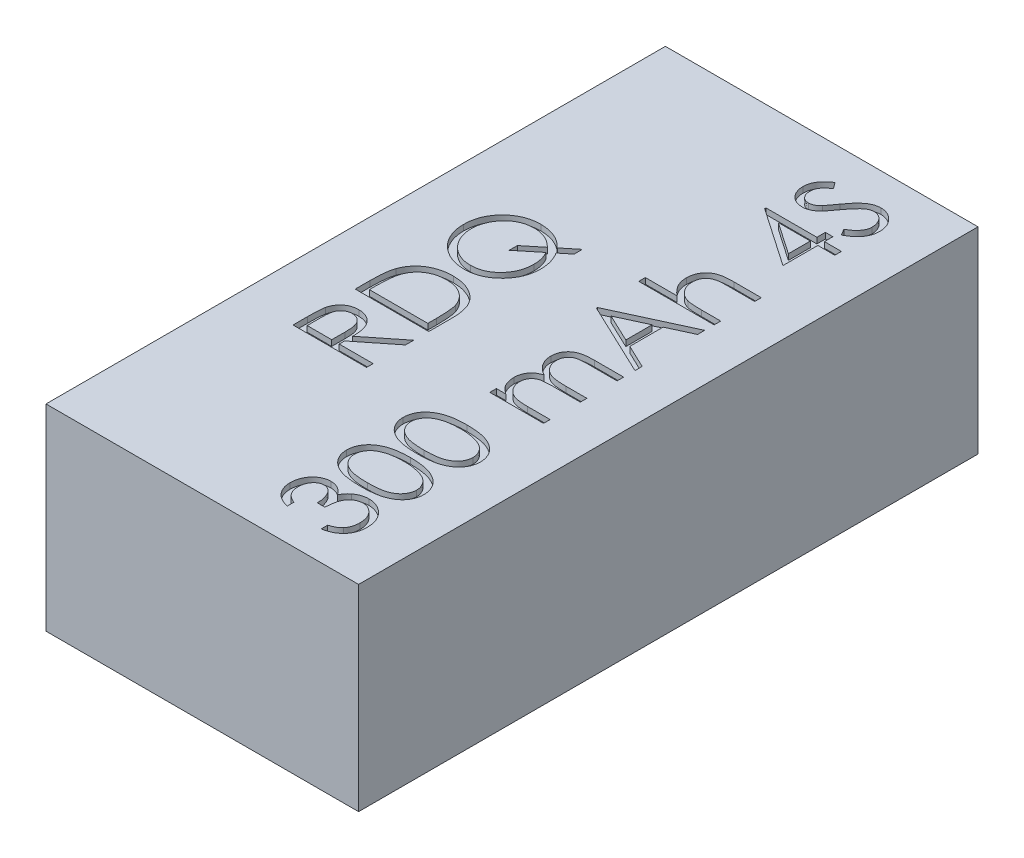
SolidWorks part; units mm, degrees
ref_plane "Front" through (0, 0, 0) normal (0, 0, 1) x (1, 0, 0)
ref_plane "Top" through (0, 0, 0) normal (0, 1, 0) x (1, 0, 0)
ref_plane "Right" through (0, 0, 0) normal (1, 0, 0) x (0, 0, -1)
sketch "Sketch1" plane through (0, 0, 0) normal (0, 0, 1) x (1, 0, 0)
  line L1 (0, 0) -> (27, 0)
  line L2 (0, 0) -> (0, 17)
  line L3 (0, 17) -> (27, 17)
  line L4 (27, 0) -> (27, 17)
  dimension "D1" = 17
  dimension "D2" = 27
extrude "Boss-Extrude1" add sketch "Sketch1" along normal blind 53.5
sketch "Sketch2" plane through (0, 17, 0) normal (0, 1, 0) x (1, 0, 0)
  line L0 (11.1135, 0) -> (11.1135, -53.5) construction
  line L1 (27, 0) -> (0, 0) construction
  line L2 (27, -53.5) -> (0, -53.5) construction
  text T0 "RDQ \r\n300 mAh 4S"
extrude "Cut-Extrude1" cut sketch "Sketch2" against normal blind 0.5
